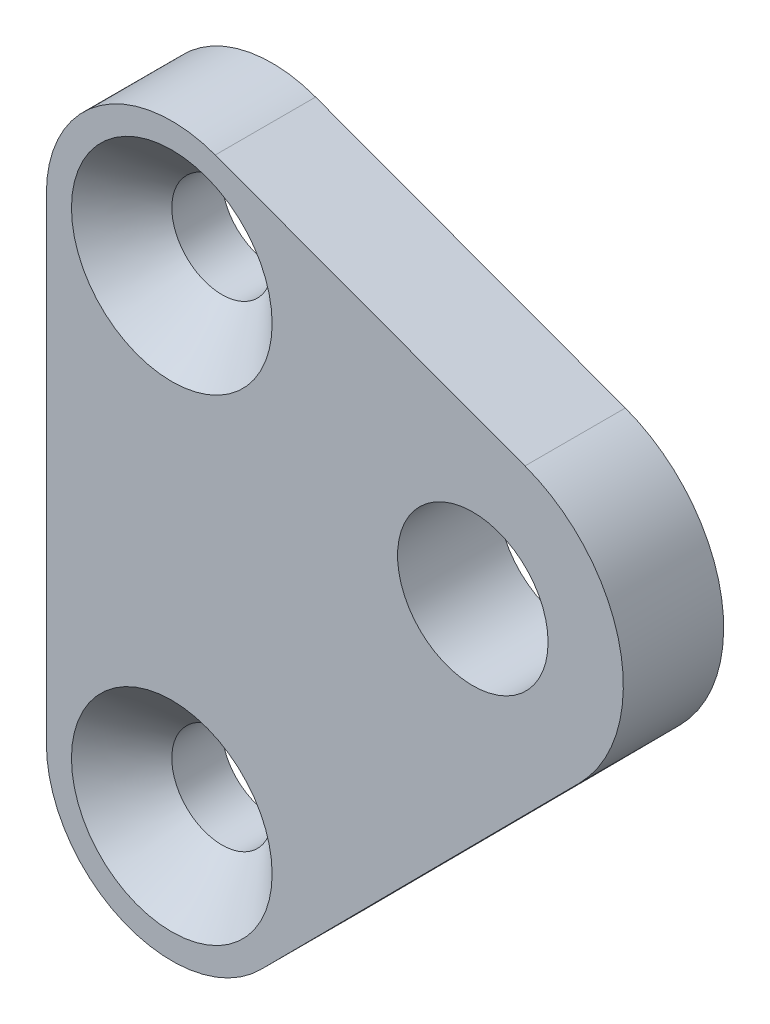
SolidWorks part; units mm, degrees
material "玻纤"
ref_plane "前视基准面" through (0, 0, 0) normal (0, 0, 1) x (1, 0, 0)
ref_plane "上视基准面" through (0, 0, 0) normal (0, 1, 0) x (1, 0, 0)
ref_plane "右视基准面" through (0, 0, 0) normal (1, 0, 0) x (0, 0, -1)
sketch "草图1" plane through (0, 0, 0) normal (0, 0, 1) x (1, 0, 0)
  line L0 (18, 9.5) -> (18, -9.5) construction
  line L1 (13, 9.5) -> (13, -9.5)
  line L2 (19.733, 14.1901) -> (32.0795, 9.6281)
  line L3 (21.5474, -13.0236) -> (34.2569, -0.2283)
  circle A0 centre (18, 9.5) radius 2
  circle A1 centre (18, -9.5) radius 2
  arc A2 (19.733, 14.1901) -> (13, 9.5) centre (18, 9.5) ccw
  arc A3 (21.5474, -13.0236) -> (13, -9.5) centre (18, -9.5) cw
  circle A4 centre (30, 4) radius 3
  arc A5 (32.0795, 9.6281) -> (34.2569, -0.2283) centre (30, 4) cw
  dimension "D4" = 4
  dimension "D5" = 5
  dimension "D6" = 30
  dimension "D7" = 6
  dimension "D8" = 6
  dimension "D1" = 18
  dimension "D2" = 9.5
  dimension "D3" = 19
  dimension "D9" = 5.5
extrude "凸台-拉伸1" add sketch "草图1" along normal blind 4
chamfer "倒角1" distance 2 angle 45 2 edges at (20, -9.5, 4) (20, 9.5, 4)
